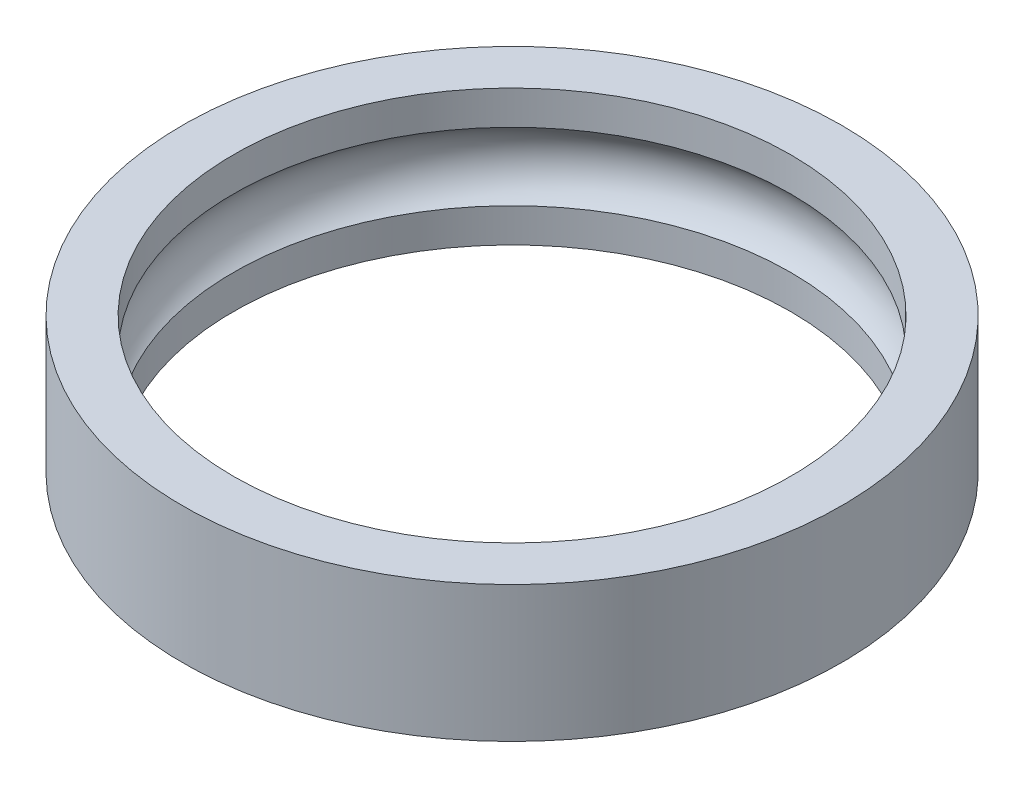
SolidWorks part; units mm, degrees
ref_plane "Front Plane" through (0, 0, 0) normal (0, 0, 1) x (1, 0, 0)
ref_plane "Top Plane" through (0, 0, 0) normal (0, 1, 0) x (1, 0, 0)
ref_plane "Right Plane" through (0, 0, 0) normal (1, 0, 0) x (0, 0, -1)
sketch "Sketch4" plane through (0, 0, 0) normal (0, 0, 1) x (1, 0, 0)
  line L0 (0, 0) -> (0, 31.3146) construction
sketch "Sketch3" plane through (0, 0, 0) normal (0, 0, 1) x (1, 0, 0)
  line L0 (25.4, 12.7) -> (-25.4, 12.7) construction
  line L1 (26.035, 9.525) -> (26.035, 3.175) construction
  line L2 (26.035, 6.35) -> (27.6225, 6.35) construction
  line L3 (26.035, 0) -> (30.7975, 0)
  line L4 (26.035, 12.7) -> (30.7975, 12.7)
  line L5 (30.7975, 12.7) -> (30.7975, 0)
  line L6 (26.035, 12.7) -> (26.035, 9.525)
  line L7 (26.035, 0) -> (26.035, 3.175)
  line L8 (27.6225, 6.35) -> (30.7975, 6.35) construction
  arc A0 (26.035, 9.525) -> (26.035, 3.175) centre (23.6537, 6.35) cw
  dimension "D2" = 3.175
  dimension "D1" = 26.035
  dimension "D3" = 1.5875
  dimension "D4" = 3.175
revolve "Revolve3" add sketch "Sketch3" angle 360 about L0
ref_plane "Plane1" through (68.58, 0, 0) normal (1, 0, 0) x (0, 0, -1)
